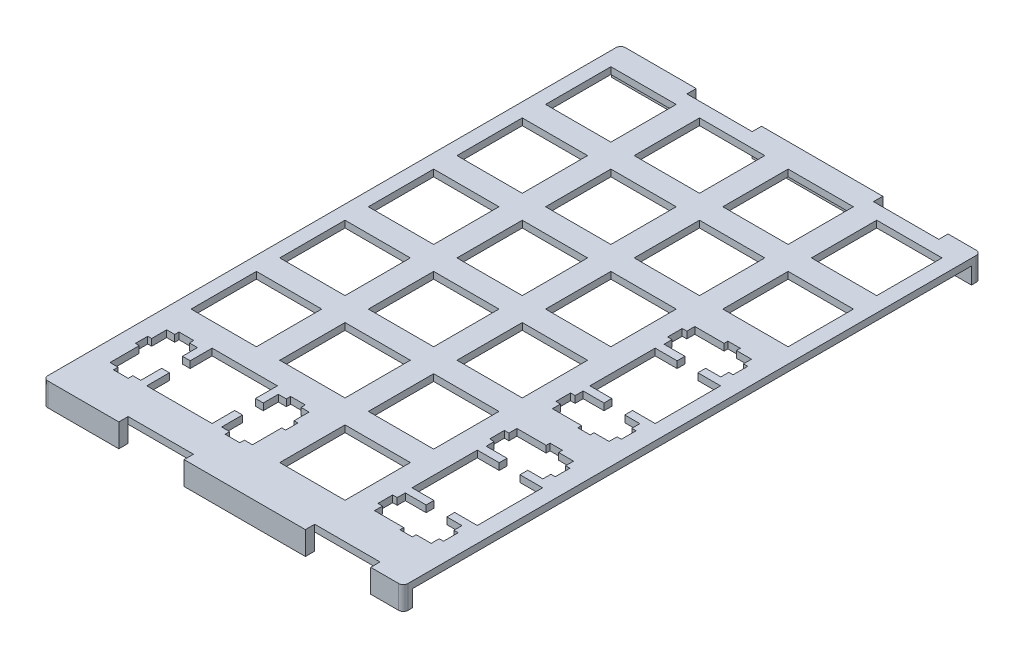
SolidWorks part; units mm, degrees
ref_plane "前视基准面" through (0, 0, 0) normal (0, 0, 1) x (1, 0, 0)
ref_plane "上视基准面" through (0, 0, 0) normal (0, 1, 0) x (1, 0, 0)
ref_plane "右视基准面" through (0, 0, 0) normal (1, 0, 0) x (0, 0, -1)
sketch "草图1" plane through (0, 0, 0) normal (0, 1, 0) x (1, 0, 0)
  line L0 (30, 0) -> (30, -57) construction
  line L1 (3, 0) -> (107, 0) construction
  line L2 (0, -3) -> (0, -117) construction
  line L3 (3, -120) -> (107, -120) construction
  line L4 (110, -3) -> (110, -117) construction
  line L5 (30, -57) -> (0, -57) construction
  line L15 (34.8, -3.2) -> (48.8, -3.2)
  line L16 (34.8, -3.2) -> (34.8, -17.2)
  line L17 (34.8, -17.2) -> (48.8, -17.2)
  line L18 (48.8, -3.2) -> (48.8, -17.2)
  line L22 (53.8, -3.2) -> (67.8, -3.2)
  line L23 (53.8, -3.2) -> (53.8, -17.2)
  line L24 (53.8, -17.2) -> (67.8, -17.2)
  line L25 (67.8, -3.2) -> (67.8, -17.2)
  line L30 (72.8, -3.2) -> (86.8, -3.2)
  line L31 (72.8, -3.2) -> (72.8, -17.2)
  line L32 (72.8, -17.2) -> (86.8, -17.2)
  line L33 (86.8, -3.2) -> (86.8, -17.2)
  line L38 (91.8, -3.2) -> (105.8, -3.2)
  line L39 (91.8, -3.2) -> (91.8, -17.2)
  line L40 (91.8, -17.2) -> (105.8, -17.2)
  line L41 (105.8, -3.2) -> (105.8, -17.2)
  line L46 (53.8, -22.2) -> (67.8, -22.2)
  line L47 (53.8, -22.2) -> (53.8, -36.2)
  line L48 (53.8, -36.2) -> (67.8, -36.2)
  line L49 (67.8, -22.2) -> (67.8, -36.2)
  line L54 (72.8, -22.2) -> (86.8, -22.2)
  line L55 (72.8, -22.2) -> (72.8, -36.2)
  line L56 (72.8, -36.2) -> (86.8, -36.2)
  line L57 (86.8, -22.2) -> (86.8, -36.2)
  line L62 (91.8, -22.2) -> (105.8, -22.2)
  line L63 (91.8, -22.2) -> (91.8, -36.2)
  line L64 (91.8, -36.2) -> (105.8, -36.2)
  line L65 (105.8, -22.2) -> (105.8, -36.2)
  line L70 (53.8, -41.2) -> (67.8, -41.2)
  line L71 (53.8, -41.2) -> (53.8, -55.2)
  line L72 (53.8, -55.2) -> (67.8, -55.2)
  line L73 (67.8, -41.2) -> (67.8, -55.2)
  line L78 (72.8, -41.2) -> (86.8, -41.2)
  line L79 (72.8, -41.2) -> (72.8, -55.2)
  line L80 (72.8, -55.2) -> (86.8, -55.2)
  line L81 (86.8, -41.2) -> (86.8, -55.2)
  line L94 (53.8, -60.2) -> (67.8, -60.2)
  line L95 (53.8, -60.2) -> (53.8, -74.2)
  line L96 (53.8, -74.2) -> (67.8, -74.2)
  line L97 (67.8, -60.2) -> (67.8, -74.2)
  line L102 (72.8, -60.2) -> (86.8, -60.2)
  line L103 (72.8, -60.2) -> (72.8, -74.2)
  line L104 (72.8, -74.2) -> (86.8, -74.2)
  line L105 (86.8, -60.2) -> (86.8, -74.2)
  line L110 (91.8, -50.7) -> (105.8, -50.7)
  line L111 (91.8, -50.7) -> (91.8, -64.7)
  line L112 (91.8, -64.7) -> (105.8, -64.7)
  line L113 (105.8, -50.7) -> (105.8, -64.7)
  line L118 (53.8, -79.2) -> (67.8, -79.2)
  line L119 (53.8, -79.2) -> (53.8, -93.2)
  line L120 (53.8, -93.2) -> (67.8, -93.2)
  line L121 (67.8, -79.2) -> (67.8, -93.2)
  line L126 (72.8, -79.2) -> (86.8, -79.2)
  line L127 (72.8, -79.2) -> (72.8, -93.2)
  line L128 (72.8, -93.2) -> (86.8, -93.2)
  line L129 (86.8, -79.2) -> (86.8, -93.2)
  line L150 (72.8, -98.2) -> (86.8, -98.2)
  line L151 (72.8, -98.2) -> (72.8, -112.2)
  line L152 (72.8, -112.2) -> (86.8, -112.2)
  line L153 (86.8, -98.2) -> (86.8, -112.2)
  line L166 (34.8, -22.2) -> (48.8, -22.2)
  line L167 (34.8, -22.2) -> (34.8, -36.2)
  line L168 (34.8, -36.2) -> (48.8, -36.2)
  line L169 (48.8, -22.2) -> (48.8, -36.2)
  line L174 (34.8, -41.2) -> (48.8, -41.2)
  line L175 (34.8, -41.2) -> (34.8, -55.2)
  line L176 (34.8, -55.2) -> (48.8, -55.2)
  line L177 (48.8, -41.2) -> (48.8, -55.2)
  line L182 (34.8, -60.2) -> (48.8, -60.2)
  line L183 (34.8, -60.2) -> (34.8, -74.2)
  line L184 (34.8, -74.2) -> (48.8, -74.2)
  line L185 (48.8, -60.2) -> (48.8, -74.2)
  line L190 (34.8, -79.2) -> (48.8, -79.2)
  line L191 (34.8, -79.2) -> (34.8, -93.2)
  line L192 (34.8, -93.2) -> (48.8, -93.2)
  line L193 (48.8, -79.2) -> (48.8, -93.2)
  line L198 (91.662, -88.7) -> (105.662, -88.7)
  line L199 (91.662, -88.7) -> (91.662, -102.7)
  line L200 (91.662, -102.7) -> (105.662, -102.7)
  line L201 (105.662, -88.7) -> (105.662, -102.7)
  line L203 (109, 1.9) -> (109, -121.9)
  line L206 (34.8, -98.2) -> (48.8, -98.2) construction
  line L207 (34.8, -98.2) -> (34.8, -112.2) construction
  line L208 (34.8, -112.2) -> (48.8, -112.2) construction
  line L209 (48.8, -98.2) -> (48.8, -112.2) construction
  line L210 (91.8, -41.2) -> (105.8, -41.2) construction
  line L211 (50, -121) -> (60, -121) construction
  line L212 (-2, 2) -> (112, 2) construction
  line L213 (-2, 2) -> (-2, -122) construction
  line L214 (-2, -122) -> (112, -122) construction
  line L215 (105.8, -41.2) -> (105.8, -55.2) construction
  line L216 (91.8, -41.2) -> (91.8, -55.2) construction
  line L217 (91.8, -55.2) -> (105.8, -55.2) construction
  line L218 (91.8, -98.2) -> (91.8, -112.2) construction
  line L219 (91.8, -98.2) -> (105.8, -98.2) construction
  line L220 (112, 2) -> (112, -122) construction
  line L221 (-2, -122) -> (10, -122) construction
  line L222 (-2, -122) -> (-2, -120) construction
  line L223 (-2, -120) -> (10, -120) construction
  line L224 (105.8, -98.2) -> (105.8, -112.2) construction
  line L225 (91.8, -112.2) -> (105.8, -112.2) construction
  line L226 (10, -122) -> (10, -120) construction
  line L228 (112, -122) -> (112, -120) construction
  line L229 (112, -120) -> (100, -120) construction
  line L230 (100, -122) -> (100, -120) construction
  line L231 (20, -122) -> (50, -122) construction
  line L232 (20, -122) -> (20, -120) construction
  line L233 (20, -120) -> (50, -120) construction
  line L234 (91.8, -60.2) -> (105.8, -60.2) construction
  line L235 (91.8, -60.2) -> (91.8, -74.2) construction
  line L236 (91.8, -74.2) -> (105.8, -74.2) construction
  line L237 (105.8, -60.2) -> (105.8, -74.2) construction
  line L238 (91.8, -79.2) -> (105.8, -79.2) construction
  line L239 (91.8, -79.2) -> (91.8, -93.2) construction
  line L240 (91.8, -93.2) -> (105.8, -93.2) construction
  line L241 (105.8, -79.2) -> (105.8, -93.2) construction
  line L242 (50, -122) -> (50, -120) construction
  line L243 (60, -122) -> (90, -122) construction
  line L244 (60, -122) -> (60, -120) construction
  line L245 (60, -120) -> (90, -120) construction
  line L246 (53.8, -98.2) -> (67.8, -98.2) construction
  line L247 (53.8, -98.2) -> (53.8, -112.2) construction
  line L248 (53.8, -112.2) -> (67.8, -112.2) construction
  line L249 (67.8, -98.2) -> (67.8, -112.2) construction
  line L254 (44.3, -98.2) -> (58.3, -98.2)
  line L255 (44.3, -98.2) -> (44.3, -112.2)
  line L256 (44.3, -112.2) -> (58.3, -112.2)
  line L257 (58.3, -98.2) -> (58.3, -112.2)
  line L258 (90, -122) -> (90, -120) construction
  line L265 (16.086, -102.441) -> (28.886, -102.441) construction
  line L269 (16.734, -61.904) -> (28.535, -61.904) construction
  line L270 (16.734, -61.904) -> (16.734, -73.904) construction
  line L271 (16.734, -73.904) -> (28.535, -73.904) construction
  line L272 (28.535, -61.904) -> (28.535, -73.904) construction
  line L286 (16.734, -80.844) -> (28.535, -80.844) construction
  line L287 (16.734, -80.844) -> (16.734, -92.844) construction
  line L288 (16.734, -92.844) -> (28.535, -92.844) construction
  line L289 (28.535, -80.844) -> (28.535, -92.844) construction
  line L296 (16.086, -102.441) -> (16.086, -109.141) construction
  line L297 (16.086, -109.141) -> (28.886, -109.141) construction
  line L298 (28.886, -102.441) -> (28.886, -109.141) construction
  line L306 (-2, -60) -> (112, -60) construction
  line L330 (31.8, -121.9) -> (31.8, 1.9)
  line L335 (55, 2) -> (55, -122) construction
  line L336 (102, -121.9) -> (102, -119.9)
  line L338 (88, -119.9) -> (88, -121.9)
  line L340 (62, -121.9) -> (62, -119.9)
  line L342 (48, -119.9) -> (48, -121.9)
  line L344 (88, -0.1) -> (88, 1.9)
  line L345 (102, -0.1) -> (88, -0.1)
  line L346 (102, 1.9) -> (102, -0.1)
  line L347 (109, 1.9) -> (102, 1.9)
  line L348 (88, 1.9) -> (62, 1.9)
  line L349 (62, 1.9) -> (62, -0.1)
  line L350 (62, -0.1) -> (48, -0.1)
  line L351 (48, -0.1) -> (48, 1.9)
  line L352 (48, 1.9) -> (31.8, 1.9)
  line L353 (48, -119.9) -> (62, -119.9)
  line L354 (88, -119.9) -> (102, -119.9)
  line L355 (102, -121.9) -> (109, -121.9)
  line L356 (62, -121.9) -> (88, -121.9)
  line L357 (31.8, -121.9) -> (48, -121.9)
  arc A238 (0, -117) -> (3, -120) centre (3, -117) ccw construction
  arc A239 (107, -120) -> (110, -117) centre (107, -117) ccw construction
  arc A240 (107, 0) -> (110, -3) centre (107, -3) cw construction
  arc A241 (3, 0) -> (0, -3) centre (3, -3) ccw construction
  point P10 (109, -80.844)
  point P27 (55, -121)
  point P34 (110, -48.5611)
  point P46 (109.1213, -114.3985)
  point P47 (109, -121.6673)
  point P48 (31.8, -116.5237)
  point P49 (31.8, -120.5447)
  point P50 (109, -63.9845)
  point P51 (109, -121)
  point P697 (110, -120)
  point P700 (110, 0)
  point P703 (0, 0)
  dimension "D13" = 2
  dimension "D18" = 2
  dimension "D19" = 2
  dimension "D20" = 2
  dimension "D27" = 30
  dimension "D28" = 10
  dimension "D29" = 30
  dimension "D30" = 10
  dimension "D31" = 2
  dimension "D53" = 4.2
  dimension "D54" = 0.1
  dimension "D55" = 0.1
  dimension "D56" = 0.1
  dimension "D57" = 0.1
  dimension "D62" = 2
  dimension "D66" = 14
  dimension "D125" = 10.859
  dimension "D126" = 16.086
  dimension "D127" = 3
  dimension "D1" = 110
  dimension "D2" = 120
  dimension "D7" = 3.2
  dimension "D8" = 57
  dimension "D11" = 30
  dimension "D15" = 3
  dimension "D21" = 2
  dimension "D22" = 6.94
  dimension "D23" = 14
  dimension "D24" = 4.2
  dimension "D25" = 2
  dimension "D26" = 10
  dimension "D32" = 114
  dimension "D33" = 124
  dimension "D40" = 2
  dimension "D43" = 2
  dimension "D44" = 1
  dimension "D45" = 14
  dimension "D47" = 19
  dimension "D48" = 19
  dimension "D50" = 28.5
  dimension "D51" = 28.5
  dimension "D52" = 38
  dimension "D58" = 14
  dimension "D59" = 14
  dimension "D60" = 0.1
  dimension "D61" = 0.1
  dimension "D67" = 14
  dimension "D99" = 14
  dimension "D100" = 14
  dimension "D113" = 4.2
  dimension "D114" = 4.338
  dimension "D119" = 12.8
  dimension "D120" = 6.7
  dimension "D140" = 12
  dimension "D141" = 11.801
  dimension "D161" = 6.265
  dimension "D162" = 4.904
  dimension "D49" = 4
  dimension "D46" = 6
extrude "凸台-拉伸1" add sketch "草图1" along normal blind 1.45
sketch "草图2" plane through (0, 0, 0) normal (0, -1, 0) x (1, 0, 0)
  line L1 (48, -1.9) -> (31.8, -1.9)
  line L2 (48, -1.9) -> (48, 0.1)
  line L3 (48, 0.1) -> (31.8, 0.1)
  line L4 (31.8, -1.9) -> (31.8, 0.1)
  line L5 (109, 121.9) -> (109, -1.9) construction
  line L6 (62, -1.9) -> (88, -1.9)
  line L7 (62, -1.9) -> (62, 0.1)
  line L8 (62, 0.1) -> (88, 0.1)
  line L9 (88, -1.9) -> (88, 0.1)
  line L10 (102, -1.9) -> (109, -1.9)
  line L11 (102, -1.9) -> (102, 0.1)
  line L12 (102, 0.1) -> (109, 0.1)
  line L13 (109, -1.9) -> (109, 0.1)
  line L14 (31.8, 121.9) -> (48, 121.9) construction
  line L15 (-946.99, 119.9) -> (49053.01, 119.9) construction
  line L16 (31.8, -1.9) -> (31.8, 121.9) construction
  line L19 (31.8, 121.9) -> (48, 121.9)
  line L20 (31.8, 121.9) -> (31.8, 119.9)
  line L21 (31.8, 119.9) -> (48, 119.9)
  line L22 (48, 121.9) -> (48, 119.9)
  line L23 (62, 121.9) -> (88, 121.9)
  line L24 (62, 121.9) -> (62, 119.9)
  line L25 (62, 119.9) -> (88, 119.9)
  line L26 (88, 121.9) -> (88, 119.9)
  line L27 (109, 121.9) -> (102, 121.9)
  line L28 (109, 121.9) -> (109, 119.9)
  line L29 (109, 119.9) -> (102, 119.9)
  line L30 (102, 121.9) -> (102, 119.9)
  line L31 (48, 0.1) -> (48, -1.9) construction
  line L32 (62, -1.9) -> (62, 0.1) construction
  line L33 (88, 0.1) -> (88, -1.9) construction
  line L34 (102, -1.9) -> (102, 0.1) construction
  line L35 (109, -1.9) -> (102, -1.9) construction
  line L36 (102, 0.1) -> (88, 0.1) construction
  line L37 (62, 119.9) -> (62, 121.9) construction
  line L38 (48, 121.9) -> (48, 119.9) construction
  line L39 (88, 121.9) -> (88, 119.9) construction
  line L40 (102, 119.9) -> (102, 121.9) construction
  line L41 (88, 119.9) -> (102, 119.9) construction
  point P20 (0, 0)
extrude "凸台-拉伸2" add sketch "草图2" along normal blind 3.55
fillet "圆角1" radius 1 4 edges at (109, -1.05, -1.9) (31.8, -1.05, -1.9) (31.8, -1.05, 121.9) (109, -1.05, 121.9)
sketch "草图5" plane through (0, 1.45, 0) normal (0, 1, 0) x (1, 0, 0)
  line L0 (44.3, -98.2) -> (44.3, -112.2) construction
  line L1 (92.03, -42.43) -> (98.3, -42.43)
  line L2 (92.03, -42.43) -> (92.03, -44.15)
  line L3 (92.03, -49.03) -> (96.5, -49.03)
  line L4 (104.18, -42.43) -> (104.18, -44.15)
  line L5 (92.03, -66.37) -> (96.5, -66.37)
  line L6 (92.03, -66.37) -> (92.03, -68.1)
  line L7 (92.03, -72.97) -> (98.3, -72.97)
  line L8 (104.18, -66.37) -> (104.18, -68.1)
  line L9 (91.892, -80.43) -> (98.162, -80.43)
  line L10 (91.892, -80.43) -> (91.892, -82.15)
  line L11 (91.892, -87.03) -> (96.362, -87.03)
  line L12 (104.042, -80.43) -> (104.042, -82.15)
  line L13 (91.892, -104.37) -> (96.362, -104.37)
  line L14 (91.892, -104.37) -> (91.892, -106.1)
  line L15 (91.892, -110.97) -> (98.162, -110.97)
  line L16 (104.042, -104.37) -> (104.042, -106.1)
  line L17 (59.97, -99.67) -> (61.69, -99.67)
  line L18 (59.97, -99.67) -> (59.97, -102.9)
  line L19 (59.97, -111.82) -> (61.69, -111.82)
  line L20 (66.57, -99.67) -> (66.57, -102.9)
  line L21 (36.03, -99.67) -> (37.76, -99.67)
  line L22 (36.03, -99.67) -> (36.03, -102.9)
  line L23 (36.03, -111.82) -> (37.76, -111.82)
  line L24 (42.63, -99.67) -> (42.63, -102.9)
  line L25 (42.63, -102.9) -> (44.3, -102.9)
  line L27 (42.63, -107.35) -> (44.3, -107.35)
  line L28 (44.3, -102.9) -> (44.3, -107.35)
  line L29 (58.3, -112.2) -> (58.3, -98.2) construction
  line L31 (37.76, -99.67) -> (37.76, -98.75)
  line L32 (37.76, -98.75) -> (40.91, -98.75)
  line L33 (40.91, -99.67) -> (40.91, -98.75)
  line L34 (36.03, -102.9) -> (35.2, -102.9)
  line L36 (36.03, -105.55) -> (35.2, -105.55)
  line L37 (35.2, -102.9) -> (35.2, -105.55)
  line L39 (37.76, -111.82) -> (37.76, -112.8)
  line L40 (37.76, -112.8) -> (40.91, -112.8)
  line L41 (40.91, -111.82) -> (40.91, -112.8)
  line L43 (61.69, -99.67) -> (61.69, -98.75)
  line L44 (61.69, -98.75) -> (64.84, -98.75)
  line L45 (64.84, -99.67) -> (64.84, -98.75)
  line L46 (59.97, -102.9) -> (58.3, -102.9)
  line L48 (59.97, -107.35) -> (58.3, -107.35)
  line L49 (58.3, -102.9) -> (58.3, -107.35)
  line L50 (64.84, -99.67) -> (66.57, -99.67)
  line L52 (61.69, -111.82) -> (61.69, -112.8)
  line L53 (61.69, -112.8) -> (64.84, -112.8)
  line L54 (64.84, -111.82) -> (64.84, -112.8)
  line L55 (64.84, -111.82) -> (66.57, -111.82)
  line L56 (59.97, -107.35) -> (59.97, -111.82)
  line L57 (42.63, -107.35) -> (42.63, -111.82)
  line L58 (40.91, -99.67) -> (42.63, -99.67)
  line L59 (36.03, -105.55) -> (36.03, -111.82)
  line L60 (40.91, -111.82) -> (42.63, -111.82)
  line L61 (91.662, -102.7) -> (105.662, -102.7) construction
  line L62 (66.57, -102.9) -> (67.4, -102.9)
  line L64 (66.57, -105.55) -> (67.4, -105.55)
  line L65 (67.4, -102.9) -> (67.4, -105.55)
  line L66 (96.362, -102.7) -> (100.812, -102.7)
  line L67 (96.362, -102.7) -> (96.362, -104.37)
  line L69 (100.812, -102.7) -> (100.812, -104.37)
  line L70 (105.662, -88.7) -> (91.662, -88.7) construction
  line L71 (91.892, -106.1) -> (90.912, -106.1)
  line L73 (91.892, -109.25) -> (90.912, -109.25)
  line L74 (90.912, -106.1) -> (90.912, -109.25)
  line L75 (104.042, -106.1) -> (104.962, -106.1)
  line L77 (104.042, -109.25) -> (104.962, -109.25)
  line L78 (104.962, -106.1) -> (104.962, -109.25)
  line L80 (98.162, -110.97) -> (98.162, -111.79)
  line L81 (98.162, -111.79) -> (100.812, -111.79)
  line L82 (100.812, -110.97) -> (100.812, -111.79)
  line L84 (96.362, -87.03) -> (96.362, -88.7)
  line L85 (96.362, -88.7) -> (100.812, -88.7)
  line L86 (100.812, -87.03) -> (100.812, -88.7)
  line L87 (91.8, -64.7) -> (105.8, -64.7) construction
  line L88 (104.042, -82.15) -> (104.962, -82.15)
  line L90 (104.042, -85.3) -> (104.962, -85.3)
  line L91 (104.962, -82.15) -> (104.962, -85.3)
  line L92 (91.892, -82.15) -> (90.912, -82.15)
  line L94 (91.892, -85.3) -> (90.912, -85.3)
  line L95 (90.912, -82.15) -> (90.912, -85.3)
  line L97 (98.3, -72.97) -> (98.3, -73.79)
  line L98 (98.3, -73.79) -> (100.95, -73.79)
  line L99 (100.95, -72.97) -> (100.95, -73.79)
  line L100 (104.18, -68.1) -> (105.1, -68.1)
  line L102 (104.18, -71.25) -> (105.1, -71.25)
  line L103 (105.1, -68.1) -> (105.1, -71.25)
  line L104 (92.03, -71.25) -> (91.05, -71.25)
  line L106 (92.03, -68.1) -> (91.05, -68.1)
  line L107 (91.05, -71.25) -> (91.05, -68.1)
  line L109 (98.3, -42.43) -> (98.3, -41.605)
  line L110 (98.3, -41.605) -> (100.95, -41.605)
  line L111 (100.95, -42.43) -> (100.95, -41.605)
  line L112 (104.18, -44.15) -> (105.1, -44.15)
  line L114 (104.18, -47.3) -> (105.1, -47.3)
  line L115 (105.1, -44.15) -> (105.1, -47.3)
  line L116 (92.03, -44.15) -> (91.05, -44.15)
  line L118 (92.03, -47.3) -> (91.05, -47.3)
  line L119 (91.05, -44.15) -> (91.05, -47.3)
  line L121 (96.5, -49.03) -> (96.5, -50.7)
  line L122 (96.5, -50.7) -> (100.95, -50.7)
  line L123 (100.95, -49.03) -> (100.95, -50.7)
  line L124 (96.5, -64.7) -> (100.95, -64.7)
  line L125 (96.5, -64.7) -> (96.5, -66.37)
  line L127 (100.95, -64.7) -> (100.95, -66.37)
  line L128 (100.95, -66.37) -> (104.18, -66.37)
  line L129 (104.18, -71.25) -> (104.18, -72.97)
  line L130 (92.03, -71.25) -> (92.03, -72.97)
  line L131 (100.95, -72.97) -> (104.18, -72.97)
  line L132 (100.812, -80.43) -> (104.042, -80.43)
  line L134 (98.162, -80.43) -> (98.162, -79.61)
  line L135 (98.162, -79.61) -> (100.812, -79.61)
  line L136 (100.812, -80.43) -> (100.812, -79.61)
  line L137 (104.042, -85.3) -> (104.042, -87.03)
  line L138 (91.892, -85.3) -> (91.892, -87.03)
  line L139 (100.812, -87.03) -> (104.042, -87.03)
  line L140 (100.812, -104.37) -> (104.042, -104.37)
  line L141 (91.892, -109.25) -> (91.892, -110.97)
  line L142 (104.042, -109.25) -> (104.042, -110.97)
  line L143 (100.812, -110.97) -> (104.042, -110.97)
  line L144 (66.57, -105.55) -> (66.57, -111.82)
  line L145 (105.8, -50.7) -> (91.8, -50.7) construction
  line L146 (100.95, -49.03) -> (104.18, -49.03)
  line L147 (100.95, -42.43) -> (104.18, -42.43)
  line L148 (92.03, -47.3) -> (92.03, -49.03)
  line L149 (104.18, -47.3) -> (104.18, -49.03)
  line L150 (91.8, -50.7) -> (91.8, -64.7) construction
  line L151 (91.662, -88.7) -> (91.662, -102.7) construction
  line L152 (58.3, -98.2) -> (44.3, -98.2) construction
  point P138 (64.84, -112.31)
  dimension "D1" = 6.6
  dimension "D2" = 6.6
  dimension "D3" = 6.6
  dimension "D4" = 6.6
  dimension "D5" = 6.6
  dimension "D6" = 6.6
  dimension "D7" = 4.45
  dimension "D8" = 4.45
  dimension "D9" = 4.45
  dimension "D10" = 4.45
  dimension "D11" = 4.45
  dimension "D12" = 4.45
  dimension "D13" = 4.7
  dimension "D14" = 1.67
  dimension "D15" = 1.67
  dimension "D16" = 4.7
  dimension "D17" = 4.7
  dimension "D18" = 1.67
  dimension "D19" = 4.7
  dimension "D20" = 1.67
  dimension "D21" = 4.7
  dimension "D22" = 4.7
  dimension "D23" = 1.67
  dimension "D24" = 1.67
  dimension "D25" = 3.23
  dimension "D26" = 3.23
  dimension "D27" = 12.15
  dimension "D28" = 12.15
  dimension "D29" = 3.15
  dimension "D30" = 3.15
  dimension "D31" = 1.73
  dimension "D32" = 1.73
  dimension "D33" = 0.98
  dimension "D34" = 0.98
  dimension "D35" = 2.65
  dimension "D36" = 3.23
  dimension "D37" = 0.83
  dimension "D38" = 1.73
  dimension "D39" = 3.15
  dimension "D40" = 0.92
  dimension "D41" = 0.92
  dimension "D42" = 3.15
  dimension "D43" = 2.65
  dimension "D44" = 3.23
  dimension "D45" = 1.73
  dimension "D46" = 0.83
  dimension "D47" = 0.98
  dimension "D48" = 3.15
  dimension "D49" = 1.72
  dimension "D50" = 6.27
  dimension "D51" = 2.65
  dimension "D52" = 0.825
  dimension "D53" = 0.92
  dimension "D54" = 1.72
  dimension "D55" = 3.15
  dimension "D56" = 12.15
  dimension "D57" = 4.47
  dimension "D58" = 2.65
  dimension "D59" = 0.82
  dimension "D60" = 6.27
  dimension "D61" = 4.47
  dimension "D62" = 12.15
  dimension "D63" = 1.72
  dimension "D64" = 1.72
  dimension "D65" = 3.15
  dimension "D66" = 3.15
  dimension "D67" = 0.98
  dimension "D68" = 0.92
  dimension "D69" = 2.65
  dimension "D70" = 6.27
  dimension "D71" = 0.82
  dimension "D72" = 12.15
  dimension "D73" = 4.47
  dimension "D74" = 0.98
  dimension "D75" = 3.15
  dimension "D76" = 3.15
  dimension "D77" = 0.92
  dimension "D78" = 1.72
  dimension "D79" = 1.72
  dimension "D80" = 2.65
  dimension "D81" = 0.82
  dimension "D82" = 6.27
  dimension "D83" = 12.15
  dimension "D84" = 3.15
  dimension "D85" = 3.15
  dimension "D86" = 0.98
  dimension "D87" = 0.92
  dimension "D88" = 1.72
  dimension "D89" = 1.72
  dimension "D90" = 4.47
extrude "切除-拉伸1" cut sketch "草图5" against normal through all
